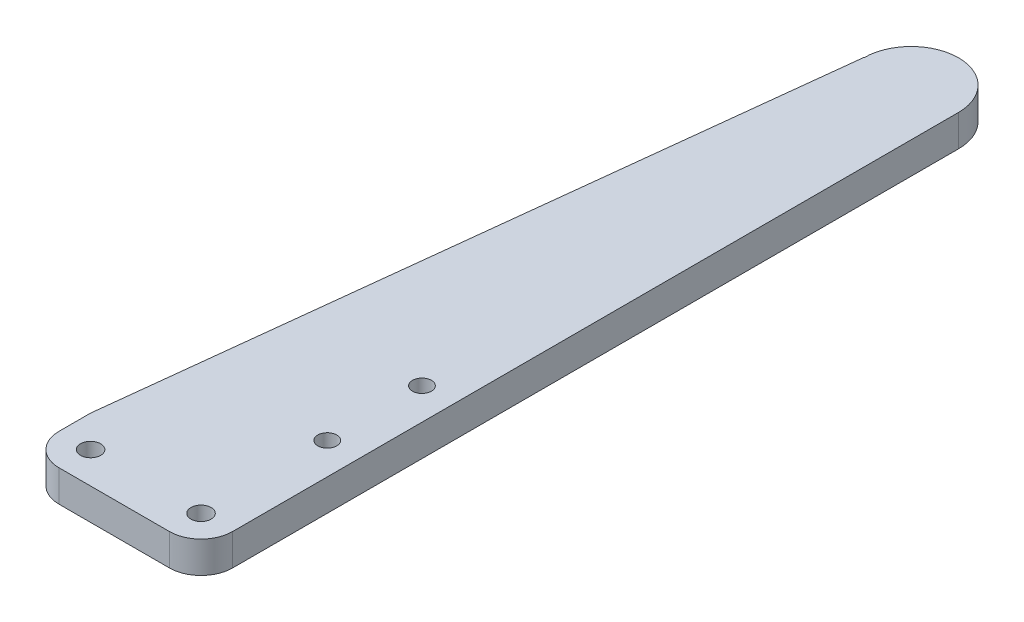
SolidWorks part; units mm, degrees
material "ﾎﾟﾘ塩化ﾋﾞﾆﾙ(PVC)硬質"
ref_plane "正面" through (0, 0, 0) normal (0, 0, 1) x (1, 0, 0)
ref_plane "平面" through (0, 0, 0) normal (0, 1, 0) x (1, 0, 0)
ref_plane "右側面" through (0, 0, 0) normal (1, 0, 0) x (0, 0, -1)
sketch "ｽｹｯﾁ1" plane through (0, 0, 0) normal (0, 1, 0) x (1, 0, 0)
  line L0 (-13.75, -55) -> (13.75, -55) construction
  line L1 (-13.75, -60) -> (13.75, -60)
  line L2 (-13.75, -60) -> (-13.75, 60)
  line L3 (-13.75, 60) -> (13.75, 60)
  line L4 (13.75, -60) -> (13.75, 60)
  line L5 (-13.75, -60) -> (13.75, 60) construction
  line L6 (-13.75, 60) -> (13.75, -60) construction
  line L7 (0, 60) -> (0, -60) construction
  line L8 (-13.75, 0) -> (13.75, 0) construction
  line L9 (-1.2024, 60.8436) -> (-13.75, -50)
  line L10 (8.75, -35) -> (8.75, -20) construction
  circle A0 centre (-8.75, -55) radius 1.6
  circle A1 centre (8.75, -55) radius 1.6
  circle A2 centre (6.25, 60) radius 7.5
  circle A3 centre (8.75, -35) radius 1.5
  circle A4 centre (8.75, -20) radius 1.5
  point P0 (0, 0)
  dimension "D1" = 5
  dimension "D2" = 5
  dimension "D3" = 17.5
  dimension "D5" = 15
  dimension "D6" = 115
  dimension "D7" = 3.2
  dimension "D9" = 5
  dimension "D10" = 3
  dimension "D11" = 25
  dimension "D4" = 5
  dimension "D8" = 15
extrude "ﾎﾞｽ - 押し出し1" add sketch "ｽｹｯﾁ1" along normal blind 5 contours L3 A2 | L3 A2 | A2 L3 L9 L2 L1 L4 A0 A1
fillet "ﾌｨﾚｯﾄ1" radius 5 2 edges at (-13.75, 2.5, 60) (13.75, 2.5, 60)
